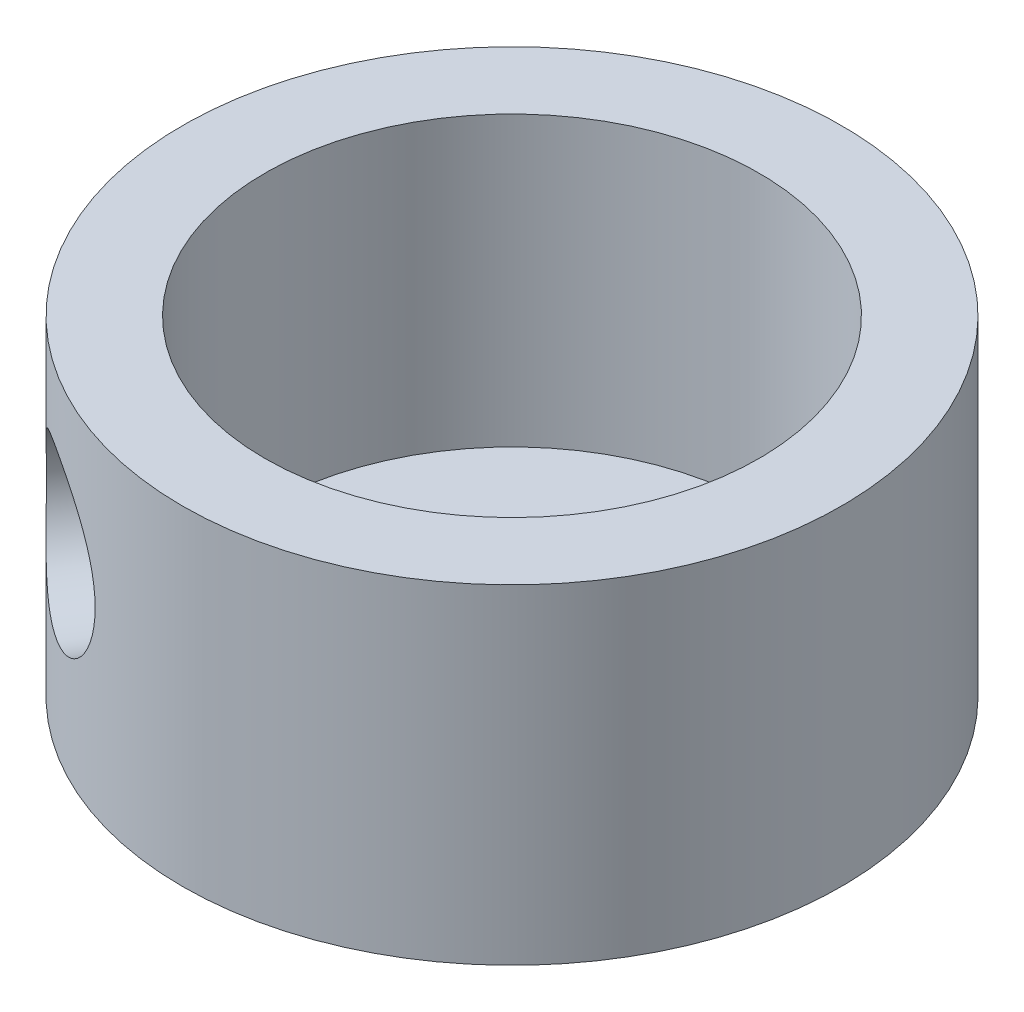
SolidWorks part; units mm, degrees
ref_plane "前基準面" through (0, 0, 0) normal (0, 0, 1) x (1, 0, 0)
ref_plane "上基準面" through (0, 0, 0) normal (0, 1, 0) x (1, 0, 0)
ref_plane "右基準面" through (0, 0, 0) normal (1, 0, 0) x (0, 0, -1)
sketch "草圖1" plane through (0, 0, 0) normal (0, 1, 0) x (1, 0, 0)
  circle A0 centre (0, 0) radius 40
  dimension "D1" = 80
extrude "填料-伸長1" add sketch "草圖1" along normal blind 40
sketch "草圖3" plane through (0, 40, 0) normal (0, 1, 0) x (1, 0, 0)
  circle A0 centre (0, 0) radius 30
  circle A1 centre (0, 0) radius 40 construction
  dimension "D1" = 10
extrude "除料-伸長2" cut sketch "草圖3" against normal blind 35
hole_wizard "Ø20.0mm 定位孔1" positions "3D草圖1" profile "草圖4" hole size "Ø20.0" standard "JIS"
sketch3d "3D草圖1"
  point P0 (-21.7448, 21.9418, 33.5733)
sketch "草圖4" plane through (-21.7448, 21.9418, 33.5733) normal (0, 1, 0) x (0.8393, 0, 0.5436)
  line L0 (0, 0) -> (0, 10)
  line L1 (0, 10) -> (10, 10)
  line L2 (10, 10) -> (10, 0)
  line L5 (10, 0) -> (0, 0)
  line L11 (0, -6.35) -> (0, 107.95) construction
  dimension "貫穿孔直徑" = 20
  dimension "貫穿孔深度" = 10
